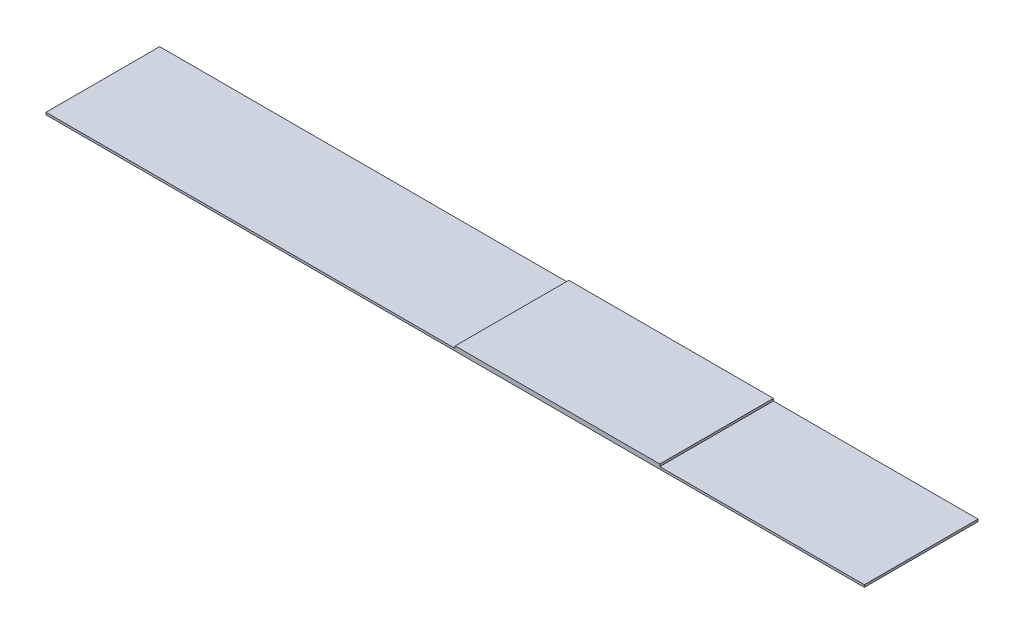
SolidWorks part; units mm, degrees
ref_plane "Front Plane" through (0, 0, 0) normal (0, 0, 1) x (1, 0, 0)
ref_plane "Top Plane" through (0, 0, 0) normal (0, 1, 0) x (1, 0, 0)
ref_plane "Right Plane" through (0, 0, 0) normal (1, 0, 0) x (0, 0, -1)
sketch "Sketch1" plane through (0, 0, 0) normal (0, 1, 0) x (1, 0, 0)
  line L1 (-18, -2.5) -> (18, -2.5)
  line L2 (-18, -2.5) -> (-18, 2.5)
  line L3 (-18, 2.5) -> (18, 2.5)
  line L4 (18, -2.5) -> (18, 2.5)
  line L5 (-18, -2.5) -> (18, 2.5) construction
  line L6 (-18, 2.5) -> (18, -2.5) construction
  point P0 (0, 0)
  dimension "D1" = 5
  dimension "D2" = 36
extrude "Boss-Extrude1" add sketch "Sketch1" along normal blind 0.1
sketch "Sketch2" plane through (0, 0.1, 0) normal (0, 1, 0) x (1, 0, 0)
  line L0 (18, 2.5) -> (-18, 2.5) construction
  line L1 (0, 2.5) -> (9, 2.5)
  line L2 (0, 2.5) -> (0, -2.5)
  line L3 (0, -2.5) -> (9, -2.5)
  line L4 (9, 2.5) -> (9, -2.5)
  line L5 (-18, -2.5) -> (18, -2.5) construction
  line L6 (18, -2.5) -> (18, 2.5) construction
  dimension "D1" = 9
  dimension "D2" = 9
extrude "Boss-Extrude2" add sketch "Sketch2" along normal blind 0.1
